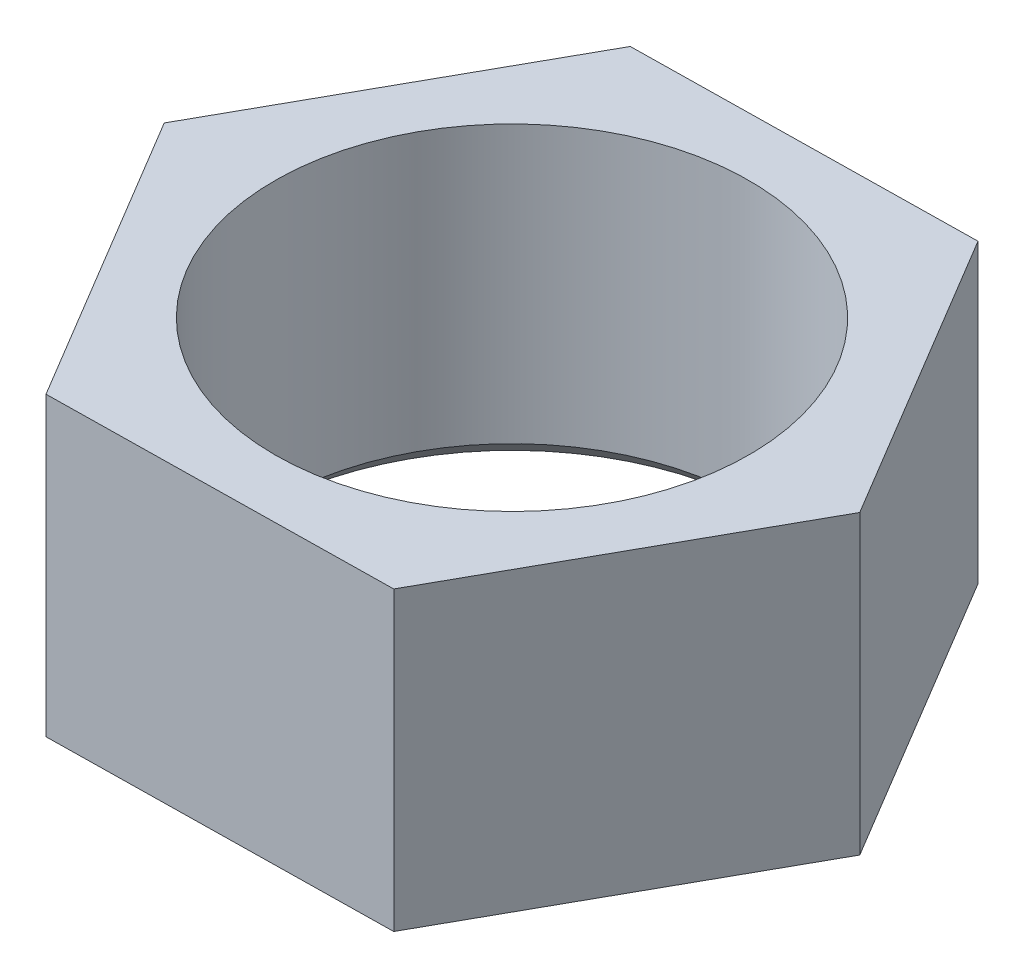
SolidWorks part; units mm, degrees
ref_plane "Front Plane" through (0, 0, 0) normal (0, 0, 1) x (1, 0, 0)
ref_plane "Top Plane" through (0, 0, 0) normal (0, 1, 0) x (1, 0, 0)
ref_plane "Right Plane" through (0, 0, 0) normal (1, 0, 0) x (0, 0, -1)
sketch "Sketch1" plane through (0, 0, 0) normal (0, 1, 0) x (1, 0, 0)
  line L1 (8.8878, -14.8663) -> (17.3185, 0.2639)
  line L2 (17.3185, 0.2639) -> (8.4307, 15.1302)
  line L3 (8.4307, 15.1302) -> (-8.8878, 14.8663)
  line L4 (-8.8878, 14.8663) -> (-17.3185, -0.2639)
  line L5 (-17.3185, -0.2639) -> (-8.4307, -15.1302)
  line L6 (-8.4307, -15.1302) -> (8.8878, -14.8663)
  circle A0 centre (0, 0) radius 15 construction
extrude "Boss-Extrude1" add sketch "Sketch1" along normal blind 15
sketch "Sketch2" plane through (0, 15, 0) normal (0, 1, 0) x (1, 0, 0)
  circle A0 centre (0, 0) radius 12
extrude "Cut-Extrude1" cut sketch "Sketch2" against normal through all
chamfer "Chamfer1" distance 1 angle 45 1 edges at (0, 0, 12)
